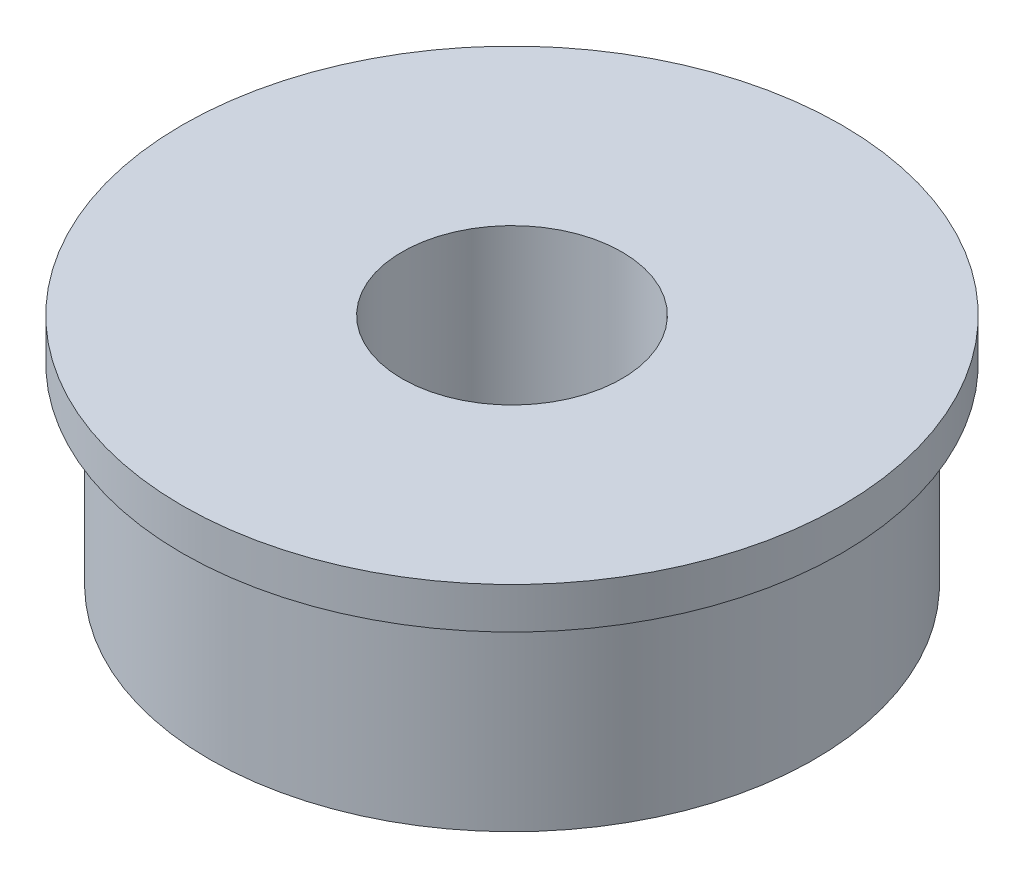
SolidWorks part; units mm, degrees
ref_plane "前视基准面" through (0, 0, 0) normal (0, 0, 1) x (1, 0, 0)
ref_plane "上视基准面" through (0, 0, 0) normal (0, 1, 0) x (1, 0, 0)
ref_plane "右视基准面" through (0, 0, 0) normal (1, 0, 0) x (0, 0, -1)
sketch "Sketch1" plane through (0, 0, 0) normal (0, 1, 0) x (1, 0, 0)
  circle A0 centre (0, 0) radius 4
  circle A1 centre (0, 0) radius 11
extrude "Boss-Extrude1" add sketch "Sketch1" along normal blind 7
sketch "Sketch2" plane through (0, 7, 0) normal (0, 1, 0) x (1, 0, 0)
  circle A0 centre (0, 0) radius 4
  circle A1 centre (0, 0) radius 12
extrude "Boss-Extrude2" add sketch "Sketch2" along normal blind 1.5
